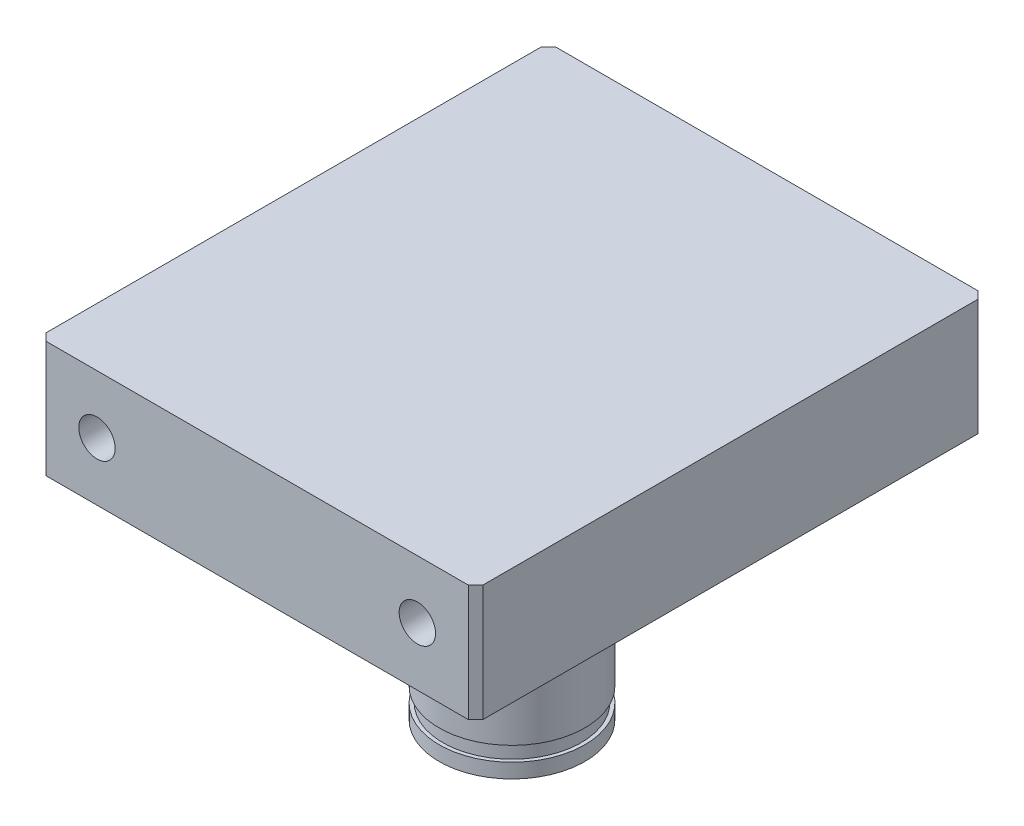
SolidWorks part; units mm, degrees
material "6061 合金"
ref_plane "前视基准面" through (0, 0, 0) normal (0, 0, 1) x (1, 0, 0)
ref_plane "上视基准面" through (0, 0, 0) normal (0, 1, 0) x (1, 0, 0)
ref_plane "右视基准面" through (0, 0, 0) normal (1, 0, 0) x (0, 0, -1)
sketch "草图1" plane through (0, 0, 0) normal (0, 1, 0) x (1, 0, 0)
  line L1 (-15, 17.5) -> (15, 17.5)
  line L2 (-15, 17.5) -> (-15, -17.5)
  line L3 (-15, -17.5) -> (15, -17.5)
  line L4 (15, 17.5) -> (15, -17.5)
  line L5 (-15, 17.5) -> (15, -17.5) construction
  line L6 (-15, -17.5) -> (15, 17.5) construction
  point P0 (0, 0)
  dimension "D1" = 35
  dimension "D2" = 30
extrude "凸台-拉伸1" add sketch "草图1" along normal blind 10
sketch "草图2" plane through (0, 0, 17.5) normal (0, 0, 1) x (1, 0, 0)
  line L0 (0, 0) -> (0, 10) construction
  line L4 (-15, 10) -> (15, 10) construction
  circle A0 centre (-11, 5) radius 1.25
  circle A1 centre (11, 5) radius 1.25
  dimension "D1" = 2.5
chamfer "倒角1" distance 0.5 angle 45 4 edges at (15, 5, -17.5) (-15, 5, -17.5) (-15, 5, 17.5) (15, 5, 17.5)
sketch "草图7" plane through (0, 0, 0) normal (0, -1, 0) x (1, 0, 0)
  line L1 (-15.5971, 18.4355) -> (15.5971, 18.4355)
  line L2 (-15.5971, 18.4355) -> (-15.5971, -18.4355)
  line L3 (-15.5971, -18.4355) -> (15.5971, -18.4355)
  line L4 (15.5971, 18.4355) -> (15.5971, -18.4355)
  line L5 (-15.5971, 18.4355) -> (15.5971, -18.4355) construction
  line L6 (-15.5971, -18.4355) -> (15.5971, 18.4355) construction
  point P0 (0, 0)
extrude "切除-拉伸4" cut sketch "草图7" against normal blind 1
sketch "草图8" plane through (0, 1, 0) normal (0, -1, 0) x (1, 0, 0)
  circle A0 centre (0, 0) radius 5
  dimension "D1" = 10
extrude "凸台-拉伸2" add sketch "草图8" along normal blind 16
sketch "草图9" plane through (0, 1, 0) normal (0, -1, 0) x (1, 0, 0)
  circle A0 centre (0, 0) radius 8.5
  circle A1 centre (0, 0) radius 5
  dimension "D1" = 17
extrude "凸台-拉伸3" add sketch "草图9" along normal blind 4
sketch "草图10" plane through (0, -3, 0) normal (0, -1, 0) x (1, 0, 0)
  circle A0 centre (0, 0) radius 5
  circle A1 centre (0, 0) radius 7.5
  dimension "D1" = 15
extrude "凸台-拉伸4" add sketch "草图10" along normal blind 2
sketch3d "3D草图2" plane through (0, 0, 0) normal (0, 0, 1) x (1, 0, 0)
  dimension "D1" = 2
sketch "草图11" plane through (0, -13, 0) normal (0, -1, 0) x (-1, 0, 0)
  circle A0 centre (0, 0) radius 5
  circle A1 centre (0, 0) radius 4.75
  dimension "D1" = 9.5
extrude "切除-拉伸5" cut sketch "草图11" along normal blind 1
hole_wizard "M3 螺纹孔1" positions "3D草图3" profile "草图12" tap size "M3" standard "GB"
sketch3d "3D草图3"
  point P0 (11, 5, 17.5)
  point P3 (-11, 5, 17.5)
sketch "草图12" plane through (11, 5, 17.5) normal (1, 0, 0) x (0, -1, 0)
  line L0 (0, 0) -> (0, 8.7511)
  line L1 (0, 8.7511) -> (1.25, 8)
  line L2 (1.25, 8) -> (1.25, 0)
  line L5 (1.25, 0) -> (0, 0)
  line L10 (0, 8.7511) -> (-1.25, 8) construction
  line L11 (0, -6.35) -> (0, 107.95) construction
  dimension "螺纹孔钻头直径" = 2.5
  dimension "螺纹孔钻头深度" = 8
  dimension "导头角度" = 118
cosmetic thread "孔螺蚊线1" parameters "D1"=6, "D2"=3
cosmetic thread "孔螺蚊线2" parameters "D1"=6, "D2"=3
mirror "镜向1" about plane through (0, 0, 0) normal (0, 0, 1) of "M3 螺纹孔1"
sketch "草图13" plane through (0, 0, -17.5) normal (0, 0, -1) x (-1, 0, 0)
  line L0 (-15, 10) -> (-15, 9)
  line L1 (-15, 1) -> (-15, 10) construction
  line L2 (-15, 9) -> (15, 9)
  line L3 (15, 10) -> (15, 1) construction
  line L4 (15, 9) -> (15, 10)
  line L5 (15, 10) -> (-15, 10)
  dimension "D1" = 1
extrude "切除-拉伸6" cut sketch "草图13" against normal through all
